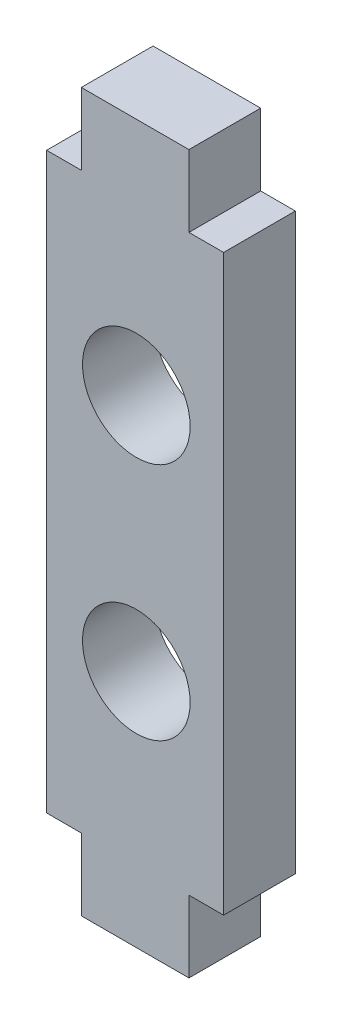
SolidWorks part; units mm, degrees
ref_plane "正面" through (0, 0, 0) normal (0, 0, 1) x (1, 0, 0)
ref_plane "平面" through (0, 0, 0) normal (0, 1, 0) x (1, 0, 0)
ref_plane "右側面" through (0, 0, 0) normal (1, 0, 0) x (0, 0, -1)
sketch "ｽｹｯﾁ1" plane through (0, 0, 0) normal (0, 0, 1) x (1, 0, 0)
  line L0 (0, 0) -> (0, 7)
  line L1 (0, 7) -> (1.45, 7)
  line L2 (1.45, 7) -> (1.45, 10)
  line L3 (1.45, 10) -> (5.95, 10)
  line L4 (5.95, 10) -> (5.95, 7)
  line L5 (5.95, 7) -> (7.4, 7)
  line L6 (7.4, 7) -> (7.4, 0)
  line L8 (0, 0) -> (0, -17)
  line L9 (0, -17) -> (1.45, -17)
  line L10 (1.45, -17) -> (1.45, -20)
  line L11 (1.45, -20) -> (5.95, -20)
  line L12 (5.95, -20) -> (5.95, -17)
  line L13 (5.95, -17) -> (7.4, -17)
  line L14 (7.4, -17) -> (7.4, 0)
  circle A0 centre (3.75, 0) radius 2.25
  circle A1 centre (3.75, -10) radius 2.25
  point P15 (0, 0)
  dimension "D8" = 4.5
  dimension "D9" = 10
  dimension "4.5" = 4.5
  dimension "D1" = 4.5
  dimension "D2" = 1.45
  dimension "D3" = 7.4
  dimension "D4" = 30
  dimension "D5" = 3
  dimension "D6" = 3
  dimension "D7" = 10
  dimension "D10" = 3.65
  dimension "D11" = 3
  dimension "D12" = 1.45
  dimension "D13" = 4.5
  dimension "D14" = 10
  dimension "D15" = 3
extrude "ﾎﾞｽ - 押し出し2" add sketch "ｽｹｯﾁ1" along normal blind 3
